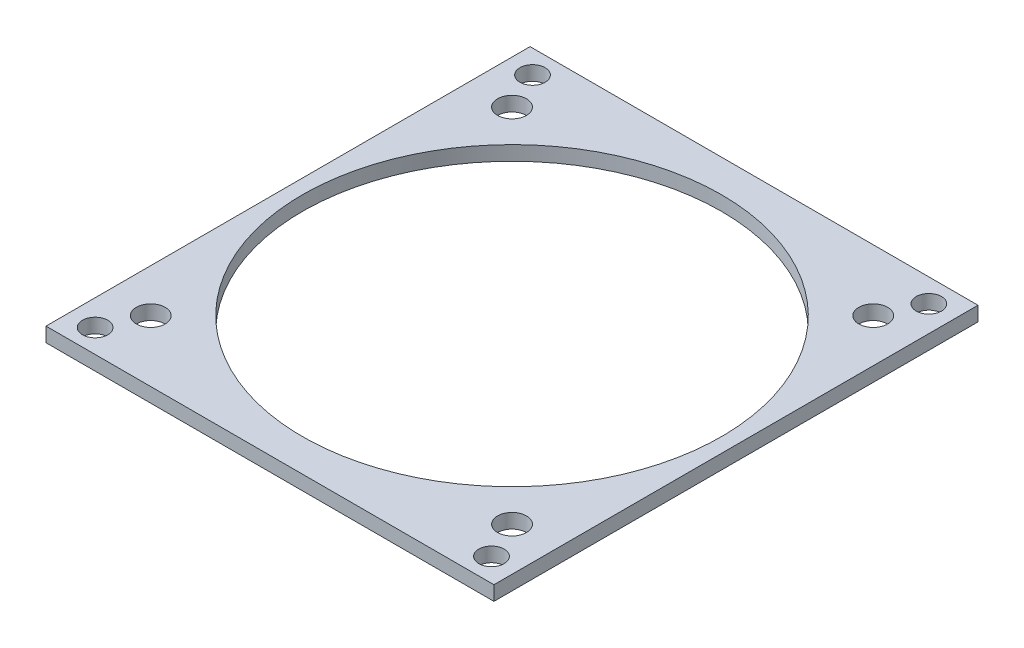
SolidWorks part; units mm, degrees
ref_plane "Спереди" through (0, 0, 0) normal (0, 0, 1) x (1, 0, 0)
ref_plane "Сверху" through (0, 0, 0) normal (0, 1, 0) x (1, 0, 0)
ref_plane "Справа" through (0, 0, 0) normal (1, 0, 0) x (0, 0, -1)
sketch "Эскиз1" plane through (0, 0, 0) normal (0, 1, 0) x (1, 0, 0)
  line L0 (0, 0) -> (0, 19.691) construction
  line L1 (-31, 33.5) -> (31, 33.5)
  line L2 (-31, 33.5) -> (-31, -33.5)
  line L3 (-31, -33.5) -> (31, -33.5)
  line L4 (31, 33.5) -> (31, -33.5)
  line L5 (-31, 33.5) -> (31, -33.5) construction
  line L6 (-31, -33.5) -> (31, 33.5) construction
  line L12 (-25, -25) -> (25, -25)
  line L13 (0, 0) -> (-17.3368, 0) construction
  line L14 (-25, -25) -> (-25, 25)
  line L15 (-25, 25) -> (25, 25)
  line L16 (25, -25) -> (25, 25)
  line L17 (-25, -25) -> (25, 25) construction
  line L18 (-25, 25) -> (25, -25) construction
  circle A0 centre (25, 25) radius 2
  circle A1 centre (-25, 25) radius 2
  circle A2 centre (25, -25) radius 2
  circle A3 centre (-25, -25) radius 2
  point P0 (0, 0)
  point P6 (0, 0)
  dimension "D5" = 4
  dimension "D1" = 62
  dimension "D2" = 67
  dimension "D3" = 50
  dimension "D4" = 50
sketch "Эскиз2" plane through (0, 0, 0) normal (0, 1, 0) x (1, 0, 0)
extrude "Бобышка-Вытянуть1" add sketch "Эскиз1" along normal blind 2 contours L4 L1 L2 L3 A3 L14 A1 L15 A0 L16 A2 L12 | A3 L12 A2 L16 A0 L15 A1 L14
sketch "Эскиз4" plane through (0, 0, 0) normal (0, -1, 0) x (1, 0, 0)
  circle A0 centre (0, 0) radius 29
  dimension "D1" = 58
extrude "Вырез-Вытянуть2" cut sketch "Эскиз4" against normal blind 2
sketch "Эскиз5" plane through (0, 0, 0) normal (0, -1, 0) x (1, 0, 0)
  line L0 (-31, -33.5) -> (-31, 33.5) construction
  line L4 (-31, 33.5) -> (31, 33.5) construction
  line L5 (0, 0) -> (13.5377, 0) construction
  line L6 (0, 0) -> (0, -16.9876) construction
  circle A0 centre (-27.43, 30.27) radius 1.75
  circle A1 centre (-27.43, -30.27) radius 1.75
  circle A2 centre (27.43, -30.27) radius 1.75
  circle A3 centre (27.43, 30.27) radius 1.75
  dimension "D3" = 3.5
  dimension "D1" = 3.57
  dimension "D2" = 3.23
extrude "Вырез-Вытянуть3" cut sketch "Эскиз5" against normal blind 2
